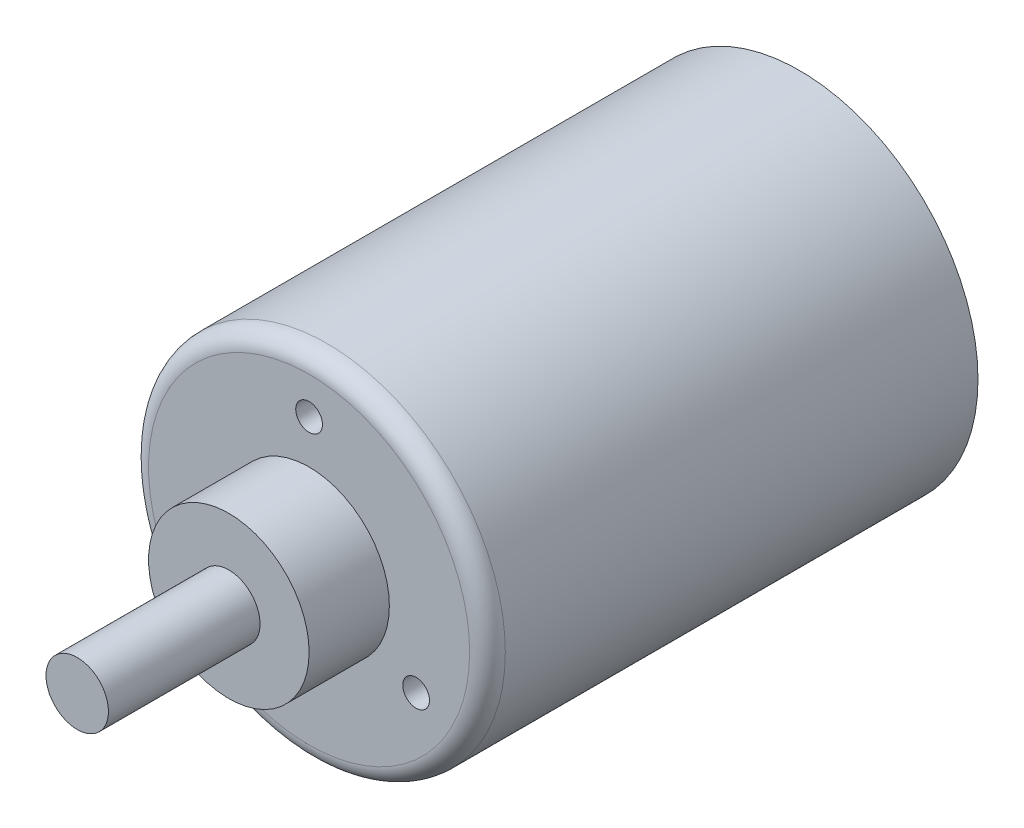
SolidWorks part; units mm, degrees
ref_plane "Front Plane" through (0, 0, 0) normal (0, 0, 1) x (1, 0, 0)
ref_plane "Top Plane" through (0, 0, 0) normal (0, 1, 0) x (1, 0, 0)
ref_plane "Right Plane" through (0, 0, 0) normal (1, 0, 0) x (0, 0, -1)
sketch "Sketch1" plane through (0, 0, 0) normal (0, 0, 1) x (1, 0, 0)
  circle A0 centre (0, 0) radius 20
  dimension "D1" = 40
extrude "Boss-Extrude1" add sketch "Sketch1" along normal blind 55
sketch "Sketch3" plane through (0, 0, 55) normal (0, 0, 1) x (1, 0, 0)
  circle A0 centre (0, 0) radius 9
  dimension "D1" = 18
extrude "Boss-Extrude2" add sketch "Sketch3" along normal blind 9
sketch "Sketch2" plane through (0, 0, 55) normal (0, 0, 1) x (1, 0, 0)
  line L0 (3.5, 0) -> (-3.5, 0) construction
  circle A0 centre (0, 0) radius 3.5
  point P7 (0, 0)
  dimension "D2" = 7
extrude "Cut-Extrude1" cut sketch "Sketch2" against normal blind 2 and the other way blind 100
sketch "Sketch6" plane through (0, 0, 53) normal (0, 0, 1) x (1, 0, 0)
  circle A2 centre (0, 0) radius 3.5
  circle A3 centre (0, 0) radius 3.5
  dimension "D1" = 0
extrude "Boss-Extrude3" add sketch "Sketch6" along normal blind 28
sketch "Sketch7" plane through (0, 0, 0) normal (0, 0, -1) x (-1, 0, 0)
  circle A2 centre (0, 0) radius 17
  circle A3 centre (0, 0) radius 17
  dimension "D1" = 3
extrude "Cut-Extrude2" cut sketch "Sketch7" against normal blind 3
fillet "Fillet2" radius 2 1 edges at (20, 0, 55)
sketch "Sketch8" plane through (0, 0, 55) normal (0, 0, 1) x (1, 0, 0)
  line L0 (0, 0) -> (-12, -6.9282) construction
  line L1 (0, 0) -> (12, -6.9282) construction
  line L2 (0, 0) -> (0, 13.8564) construction
  line L3 (-12, -6.9282) -> (0, 13.8564) construction
  circle A0 centre (0, 0) radius 13.8564 construction
  circle A1 centre (0, 13.8564) radius 1.5
  circle A2 centre (-12, -6.9282) radius 1.5
  circle A3 centre (12, -6.9282) radius 1.5
  dimension "D4" = 3
  dimension "D1" = 120
  dimension "D2" = 120
  dimension "D3" = 24
extrude "Cut-Extrude3" cut sketch "Sketch8" against normal blind 5
